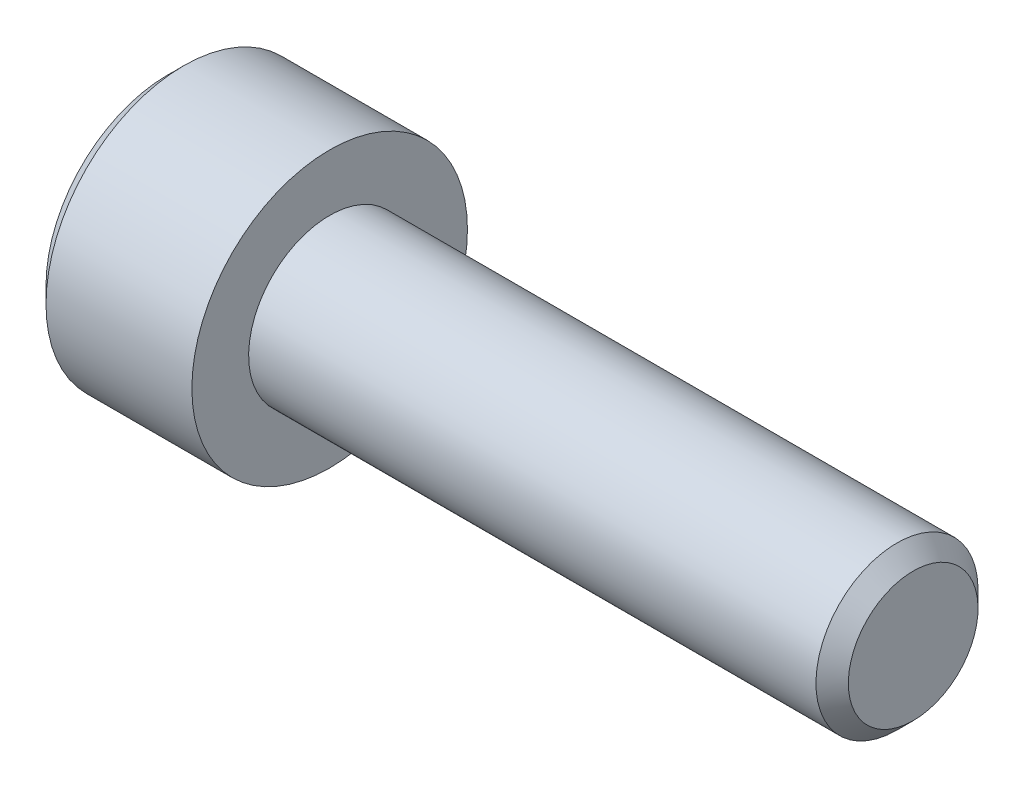
SolidWorks part; units mm, degrees
ref_plane "Front" through (0, 0, 0) normal (0, 0, 1) x (1, 0, 0)
ref_plane "Top" through (0, 0, 0) normal (0, 1, 0) x (1, 0, 0)
ref_plane "Right" through (0, 0, 0) normal (1, 0, 0) x (0, 0, -1)
ref_plane "Plane1" through (0, 0, 0) normal (0, 0, 1) x (1, 0, 0)
sketch "Sketch1" plane through (0, 0, 0) normal (0, 0, 1) x (1, 0, 0)
  line L0 (-5, 0) -> (-5, 3.75)
  line L1 (-5, 3.75) -> (-4.5, 4.25)
  line L2 (-4.5, 4.25) -> (0, 4.25)
  line L3 (0, 4.25) -> (0, 2.5)
  line L4 (0, 2.5) -> (18, 2.5)
  line L6 (18, 2.5) -> (18, 0)
  line L7 (18, 0) -> (-5, 0)
  line L8 (18, 0) -> (-5, 0) construction
  dimension "D1" = 2.5
  dimension "D2" = 18
  dimension "D3" = 5
  dimension "D4" = 4.25
revolve "Revolve1" add sketch "Sketch1" angle 360 about L8
ref_plane "Plane2" through (0, 0, 0) normal (0, 0, 1) x (1, 0, 0)
chamfer "Chamfer1" distance 0.5 angle 45 1 edges at (18, -2.5, 0)
sketch "Sketch2" plane through (0, 0, 0) normal (0, 0, 1) x (1, 0, 0)
  line L0 (-5, 0) -> (-5, 2)
  line L1 (-5, 2) -> (-2.5, 2)
  line L2 (-2.5, 2) -> (-1.9641, 0)
  line L3 (-1.9641, 0) -> (-5, 0)
  line L4 (-1.9641, 0) -> (-5, 0) construction
revolve "Cut-Revolve1" cut sketch "Sketch2" angle 360 about L4
ref_plane "Plane3" through (-5, 0, 0) normal (1, 0, 0) x (0, 0, -1)
sketch "Sketch3" plane through (-5, 0, 0) normal (1, 0, 0) x (0, 0, -1)
  line L0 (-2, 1.1547) -> (-2, -1.1547)
  line L1 (-2, -1.1547) -> (0, -2.3094)
  line L2 (0, -2.3094) -> (2, -1.1547)
  line L3 (2, -1.1547) -> (2, 1.1547)
  line L4 (2, 1.1547) -> (0, 2.3094)
  line L5 (0, 2.3094) -> (-2, 1.1547)
extrude "Cut-Extrude1" cut sketch "Sketch3" along normal blind 2.5
